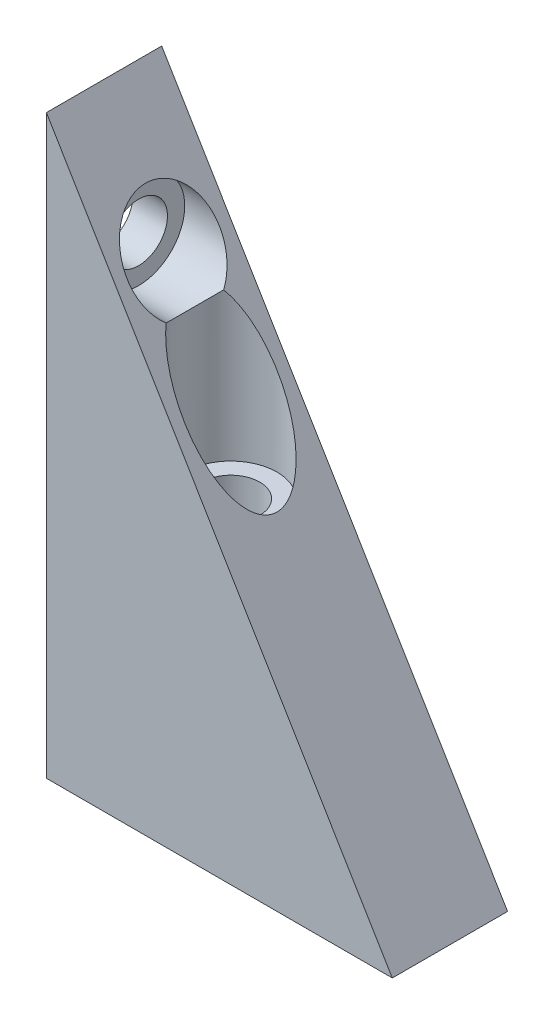
SolidWorks part; units mm, degrees
ref_plane "前视基准面" through (0, 0, 0) normal (0, 0, 1) x (1, 0, 0)
ref_plane "上视基准面" through (0, 0, 0) normal (0, 1, 0) x (1, 0, 0)
ref_plane "右视基准面" through (0, 0, 0) normal (1, 0, 0) x (0, 0, -1)
other "Configuration Table"
sketch "草图1" plane through (0, 0, 0) normal (0, 0, 1) x (1, 0, 0)
  line L0 (0, 0) -> (0, 50)
  line L1 (0, 50) -> (30, 0)
  line L2 (30, 0) -> (0, 0)
  dimension "D1" = 30
  dimension "D2" = 50
extrude "凸台-拉伸1" add sketch "草图1" along normal blind 10
sketch "草图2" plane through (0, 0, 0) normal (0, -1, 0) x (1, 0, 0)
  line L0 (-1.5872, 5) -> (31.4284, 5) construction
  line L1 (0, 0) -> (30, 0) construction
  line L2 (0, 10) -> (30, 10) construction
  line L3 (0, 10) -> (0, 0) construction
  circle A0 centre (11, 5) radius 2.5
  dimension "D2" = 5
  dimension "D1" = 11
extrude "切除-拉伸1" cut sketch "草图2" against normal through all
sketch "草图3" plane through (0, 0, 0) normal (-1, 0, 0) x (0, 0, 1)
  line L0 (5, -1.8108) -> (5, 51.5968) construction
  line L1 (10, 50) -> (10, 0) construction
  line L2 (0, 50) -> (0, 0) construction
  line L3 (10, 0) -> (0, 0) construction
  circle A0 centre (5, 40) radius 2.5
  dimension "D2" = 5
  dimension "D1" = 40
extrude "切除-拉伸2" cut sketch "草图3" against normal through all
ref_plane "基准面1" through (0, 50, 0) normal (0, -1, 0) x (-1, 0, 0)
sketch "草图4" plane through (0, 50, 0) normal (0, -1, 0) x (-1, 0, 0)
  circle A0 centre (-11, -5) radius 4
  dimension "D1" = 8
extrude "切除-拉伸3" cut sketch "草图4" along normal blind 26
ref_plane "基准面2" through (30, 0, 0) normal (-1, 0, 0) x (0, 0, 1)
sketch "草图5" plane through (30, 0, 0) normal (-1, 0, 0) x (0, 0, 1)
  circle A0 centre (5, 40) radius 4
  dimension "D1" = 8
extrude "切除-拉伸4" cut sketch "草图5" along normal blind 27
